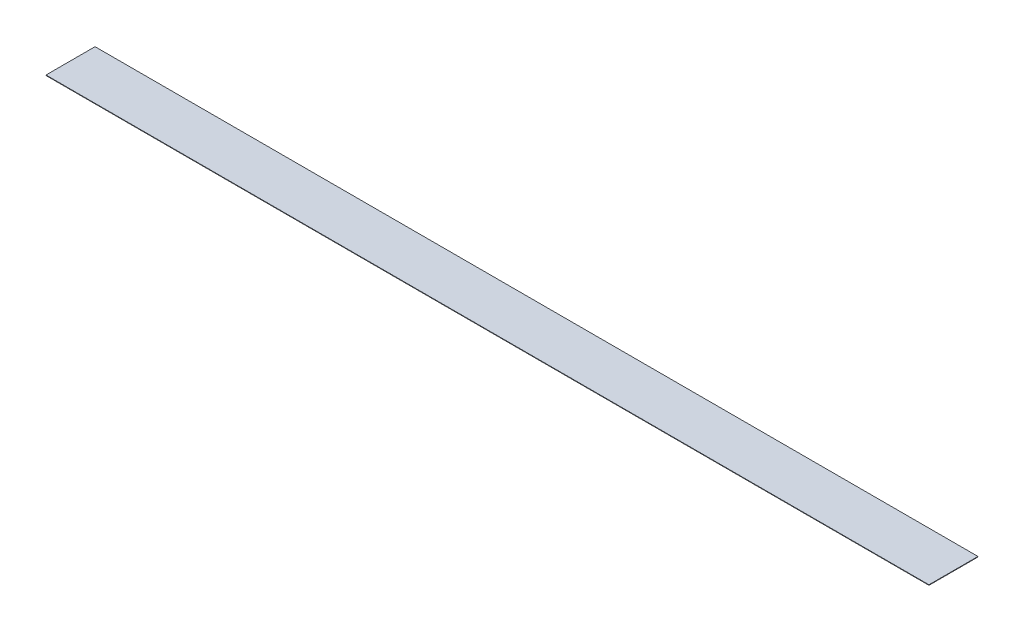
SolidWorks part; units mm, degrees
ref_plane "Front Plane" through (0, 0, 0) normal (0, 0, 1) x (1, 0, 0)
ref_plane "Top Plane" through (0, 0, 0) normal (0, 1, 0) x (1, 0, 0)
ref_plane "Right Plane" through (0, 0, 0) normal (1, 0, 0) x (0, 0, -1)
sketch "Sketch1" plane through (0, 0, 0) normal (0, 1, 0) x (1, 0, 0)
  line L1 (-114.3, 6.35) -> (114.3, 6.35)
  line L2 (-114.3, 6.35) -> (-114.3, -6.35)
  line L3 (-114.3, -6.35) -> (114.3, -6.35)
  line L4 (114.3, 6.35) -> (114.3, -6.35)
  line L5 (-114.3, 6.35) -> (114.3, -6.35) construction
  line L6 (-114.3, -6.35) -> (114.3, 6.35) construction
  point P0 (0, 0)
  dimension "D1" = 12.7
  dimension "D2" = 228.6
extrude "Boss-Extrude1" add sketch "Sketch1" along normal blind 0.125
